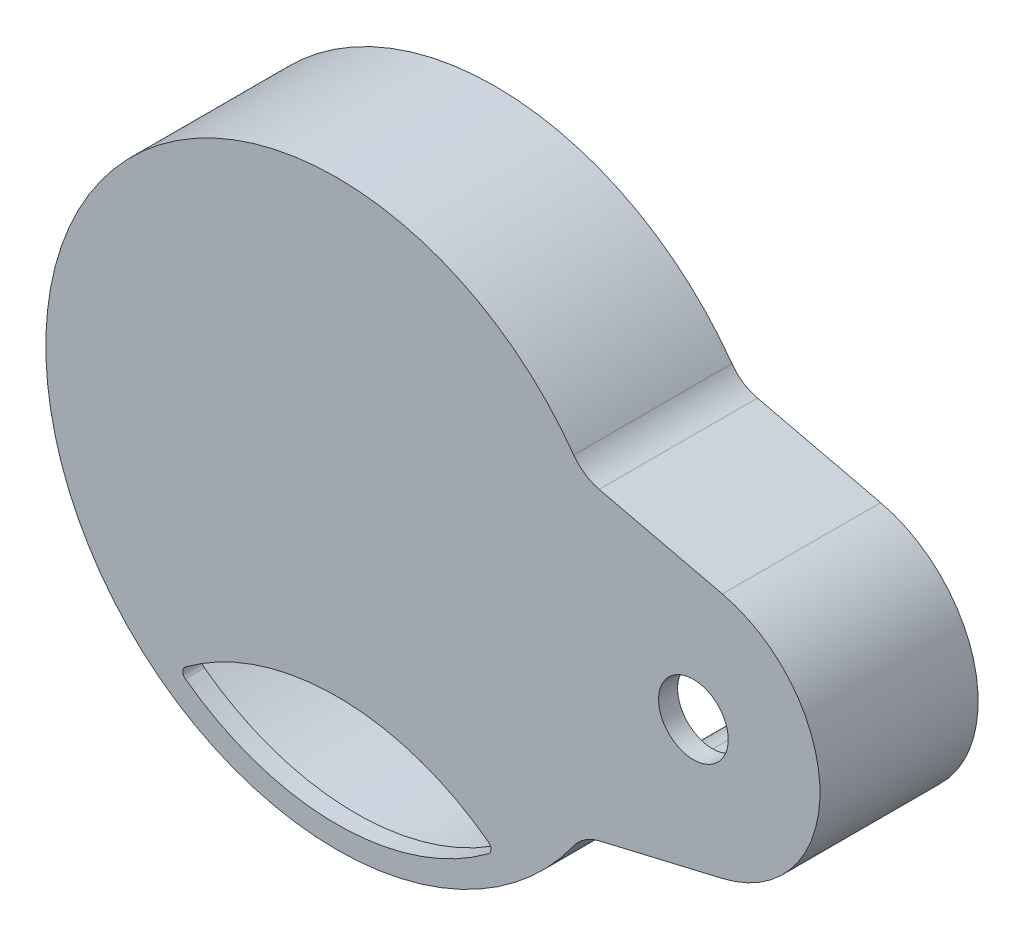
SolidWorks part; units mm, degrees
ref_plane "Alzado" through (0, 0, 0) normal (0, 0, 1) x (1, 0, 0)
ref_plane "Planta" through (0, 0, 0) normal (0, 1, 0) x (1, 0, 0)
ref_plane "Vista lateral" through (0, 0, 0) normal (1, 0, 0) x (0, 0, -1)
sketch "Croquis1" plane through (0, 0, 0) normal (0, 0, 1) x (1, 0, 0)
  line L0 (40.7586, 21.1287) -> (60.227, 16.5481)
  line L1 (60.227, -16.5481) -> (40.7586, -21.1287)
  line L2 (41.4457, 24.049) -> (60.9141, 19.4684)
  line L3 (60.9141, -19.4684) -> (41.4457, -24.049)
  arc A0 (34.9857, 25) -> (34.9857, -25) centre (0, 0) ccw
  arc A1 (37.4266, 26.7442) -> (37.4266, -26.7442) centre (0, 0) ccw
  circle A2 centre (0, 0) radius 41.3335 construction
  circle A3 centre (56.3335, 0) radius 15 construction
  arc A4 (60.227, 16.5481) -> (60.227, -16.5481) centre (56.3335, 0) cw
  arc A5 (34.9857, 25) -> (40.7586, 21.1287) centre (43.0203, 30.7413) ccw
  arc A6 (40.7586, -21.1287) -> (34.9857, -25) centre (43.0203, -30.7413) ccw
  arc A7 (37.4266, 26.7442) -> (41.4457, 24.049) centre (43.0203, 30.7413) ccw
  arc A8 (60.9141, 19.4684) -> (60.9141, -19.4684) centre (56.3335, 0) cw
  arc A9 (41.4457, -24.049) -> (37.4266, -26.7442) centre (43.0203, -30.7413) ccw
  point P14 (43.407, 22.8452)
  point P15 (35.2747, 24.5905)
  point P16 (35.5417, -24.203)
  point P17 (40.8318, -21.1841)
  point P18 (0, 0)
  point P22 (0, 0)
  point P30 (0, 0)
  dimension "D1" = 3
  dimension "D2" = 86
  dimension "D3" = 82.667
  dimension "D4" = 30
  dimension "D5" = 2
  dimension "D6" = 20
  dimension "D7" = 50
  dimension "D8" = 3
extrude "Saliente-Extruir1" add sketch "Croquis1" along normal blind 25
sketch "Croquis2" plane through (0, 0, 25) normal (0, 0, 1) x (1, 0, 0)
  line L2 (41.4457, -24.049) -> (60.9141, -19.4684)
  line L3 (60.9141, 19.4684) -> (41.4457, 24.049)
  line L4 (41.4457, -24.049) -> (60.9141, -19.4684)
  line L5 (60.9141, 19.4684) -> (41.4457, 24.049)
  arc A4 (41.4457, -24.049) -> (37.4266, -26.7442) centre (43.0203, -30.7413) ccw
  arc A5 (60.9141, -19.4684) -> (60.9141, 19.4684) centre (56.3335, 0) ccw
  arc A6 (37.4266, 26.7442) -> (41.4457, 24.049) centre (43.0203, 30.7413) ccw
  arc A7 (37.4266, 26.7442) -> (37.4266, -26.7442) centre (0, 0) ccw
  arc A8 (41.4457, -24.049) -> (37.4266, -26.7442) centre (43.0203, -30.7413) ccw
  arc A9 (60.9141, -19.4684) -> (60.9141, 19.4684) centre (56.3335, 0) ccw
  arc A10 (37.4266, 26.7442) -> (41.4457, 24.049) centre (43.0203, 30.7413) ccw
  arc A11 (37.4266, 26.7442) -> (37.4266, -26.7442) centre (0, 0) ccw
  dimension "D1" = 0
extrude "Saliente-Extruir2" add sketch "Croquis2" against normal blind 3
sketch "Croquis3" plane through (0, 0, 25) normal (0, 0, 1) x (1, 0, 0)
  arc A0 (-23.9477, -34.5628) -> (-23.9477, -32.9608) centre (-23.349, -33.7618) cw
  arc A1 (-23.9477, -32.9608) -> (23.9477, -32.9608) centre (0, -65) cw
  arc A2 (23.9477, -32.9608) -> (23.9477, -34.5628) centre (23.349, -33.7618) cw
  arc A3 (23.9477, -34.5628) -> (-23.9477, -34.5628) centre (0, -2.5236) cw
  point P7 (-24.349, -33.7618)
  point P9 (0, 0)
  point P10 (24.349, -33.7618)
  point P11 (0, -25)
  dimension "D2" = 1
  dimension "D1" = 40
  dimension "D4" = 25
  dimension "D3" = 48.698
extrude "Cortar-Extruir1" cut sketch "Croquis3" against normal blind 3
sketch "Croquis4" plane through (0, 0, 25) normal (0, 0, 1) x (1, 0, 0)
  circle A0 centre (56.3335, 0) radius 5.5
  dimension "D1" = 11
extrude "Cortar-Extruir2" cut sketch "Croquis4" against normal blind 3
